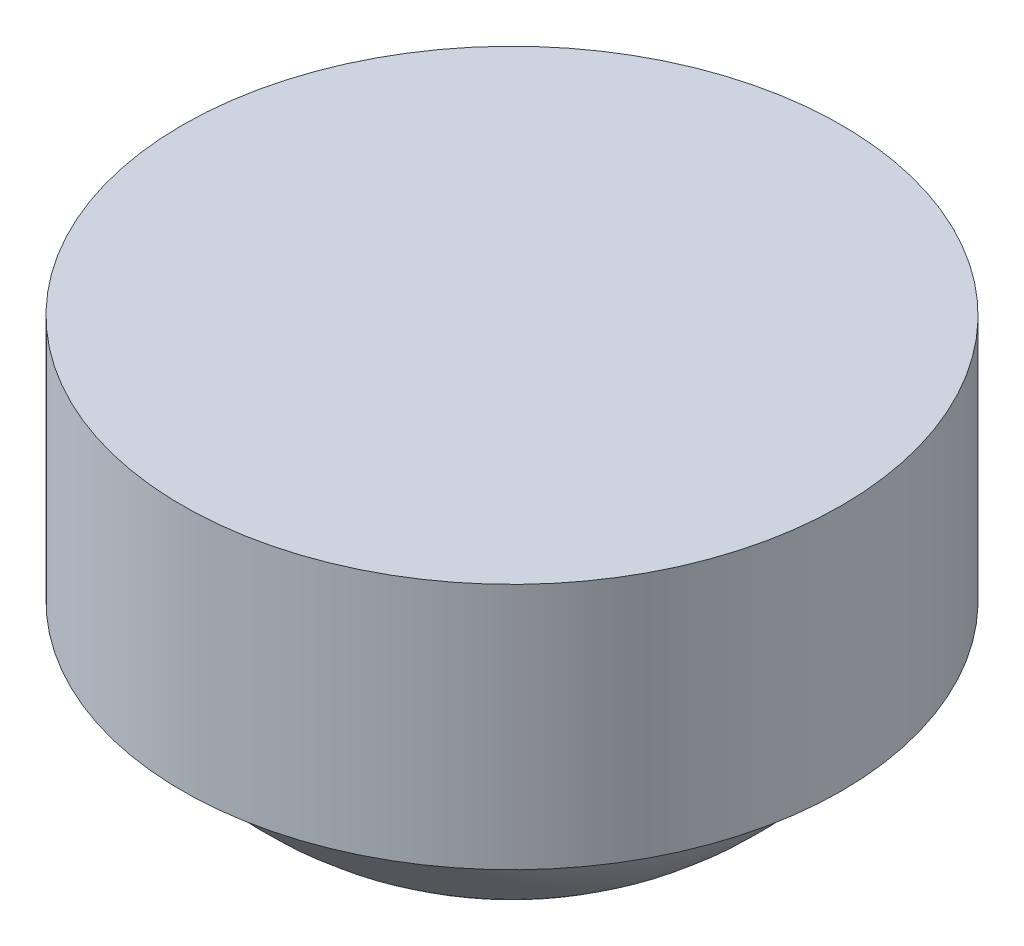
SolidWorks part; units mm, degrees
ref_plane "Front Plane" through (0, 0, 0) normal (0, 0, 1) x (1, 0, 0)
ref_plane "Top Plane" through (0, 0, 0) normal (0, 1, 0) x (1, 0, 0)
ref_plane "Right Plane" through (0, 0, 0) normal (1, 0, 0) x (0, 0, -1)
sketch "Sketch1" plane through (0, 0, 0) normal (0, 0, 1) x (1, 0, 0)
  line L0 (20, -67) -> (0, -67)
  line L1 (0, -67) -> (0, -93)
  line L2 (18.4662, -82) -> (20, -82)
  line L3 (20, -82) -> (20, -67)
  line L4 (0, -67) -> (0, -93) construction
  arc A0 (0, -93) -> (18.4662, -82) centre (0, -72) ccw
  point P6 (0, 0)
  point P7 (0, 0)
  point P8 (0, 0)
  point P9 (0, 0)
  point P10 (0, 0)
  dimension "D3" = 21
  dimension "D1" = 20
  dimension "D2" = 26
  dimension "D4" = 15
revolve "Revolve1" add sketch "Sketch1" angle 360 about L4
